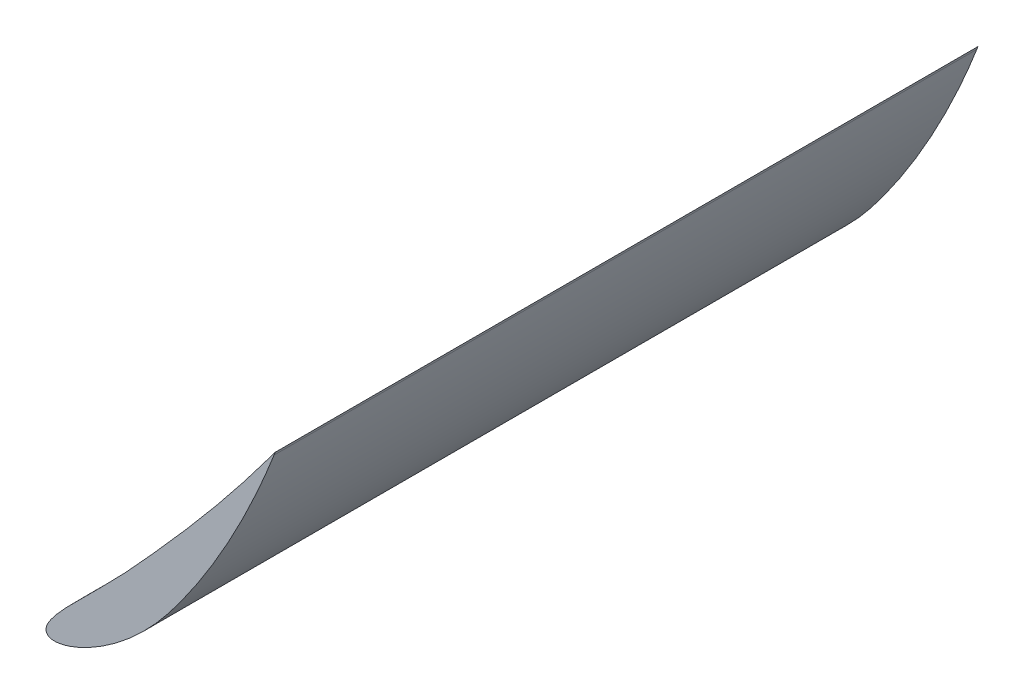
SolidWorks part; units mm, degrees
ref_plane "Front Plane" through (0, 0, 0) normal (0, 0, 1) x (1, 0, 0)
ref_plane "Top Plane" through (0, 0, 0) normal (0, 1, 0) x (1, 0, 0)
ref_plane "Right Plane" through (0, 0, 0) normal (1, 0, 0) x (0, 0, -1)
sketch "Sketch1" plane through (0, 0, 0) normal (0, 0, 1) x (1, 0, 0)
  line L12 (81.634, 97.2876) -> (0, 0) construction
  line L13 (81.5114, 97.3905) -> (81.7566, 97.1848) construction
  line L15 (0, 0) -> (49.9996, 0) construction
  line L16 (81.5114, 97.3905) -> (82.1927, 98.3086)
  line L17 (81.7566, 97.1848) -> (82.1927, 98.3086)
  spline S1 degree 3 poles (81.7566, 97.1848) (81.7317, 97.1205) (81.6321, 96.864) (81.4077, 96.2892) (81.0334, 95.3367) (80.5075, 94.0156) (79.829, 92.3376) (78.9965, 90.3178) (78.0086, 87.974) (76.8643, 85.3265) (75.5632, 82.3981) (74.105, 79.2134) (72.4912, 75.7986) (70.7234, 72.1816) (68.8046, 68.3914) (66.7394, 64.4574) (64.5329, 60.4101) (62.192, 56.2804) (59.7244, 52.0991) (57.1391, 47.8973) (54.4471, 43.705) (51.6593, 39.5528) (48.7894, 35.4693) (45.8491, 31.4847) (42.8637, 27.6176) (39.7792, 23.949) (36.6227, 20.4984) (33.4183, 17.2831) (30.1932, 14.317) (26.9767, 11.6105) (23.7993, 9.1714) (20.6932, 7.004) (17.6904, 5.1108) (14.8237, 3.491) (12.1246, 2.1423) (9.6232, 1.0613) (7.3474, 0.2422) (5.3215, -0.3201) (3.5651, -0.6329) (2.09, -0.7009) (0.8965, -0.5251) (-0.0134, -0.0818) (-0.579, 0.6607) (-0.6886, 1.6321) (-0.4133, 2.7429) (0.1968, 4.0285) (1.138, 5.5031) (2.4006, 7.1704) (3.9718, 9.0291) (5.834, 11.0763) (7.9665, 13.3081) (10.3447, 15.7209) (12.9427, 18.3096) (15.7314, 21.0695) (18.6806, 23.9946) (21.7585, 27.0784) (24.933, 30.313) (28.1717, 33.6891) (31.4437, 37.1956) (34.7151, 40.8229) (38.0269, 44.4942) (41.3443, 48.201) (44.6452, 51.9215) (47.9049, 55.6368) (51.1016, 59.325) (54.2144, 62.9647) (57.224, 66.5334) (60.1133, 70.0079) (62.8659, 73.3655) (65.468, 76.5829) (67.9066, 79.6376) (70.1703, 82.5079) (72.2485, 85.1731) (74.1325, 87.6134) (75.814, 89.8111) (77.286, 91.7497) (78.542, 93.415) (79.577, 94.7947) (80.3867, 95.8784) (80.9673, 96.6583) (81.3169, 97.1284) (81.4725, 97.338) (81.5114, 97.3905) knots 0 0 0 0 0.000791 0.00316 0.007087 0.012544 0.019489 0.027873 0.037633 0.048699 0.060994 0.074433 0.088923 0.104368 0.120665 0.13771 0.155392 0.173601 0.192223 0.211146 0.230254 0.249435 0.268577 0.287568 0.306301 0.324671 0.342595 0.359992 0.376786 0.392898 0.408252 0.422771 0.43638 0.449003 0.46057 0.471014 0.48028 0.488325 0.495133 0.500728 0.505217 0.508863 0.51207 0.515471 0.519696 0.525078 0.53175 0.539754 0.54908 0.559692 0.571531 0.584528 0.598598 0.61365 0.629586 0.6463 0.663686 0.681632 0.700027 0.718761 0.737727 0.756809 0.775888 0.794846 0.813569 0.83194 0.849847 0.86718 0.883834 0.899707 0.914701 0.928723 0.941687 0.953513 0.964128 0.973465 0.981467 0.988083 0.993272 0.997002 0.999249 1 1 1 1
  point P10 (81.634, 97.2876)
  dimension "D1" = 50
  dimension "D2" = 127
extrude "Boss-Extrude1" add sketch "Sketch1" along normal blind 254
sketch "Sketch2" plane through (0, 0, 254) normal (0, 0, 1) x (1, 0, 0)
  line L0 (81.5114, 97.3905) -> (81.7566, 97.1848) construction
  line L1 (81.634, 97.2876) -> (0, 0) construction
  line L2 (81.7566, 97.1848) -> (82.1927, 98.3086)
  line L3 (82.1927, 98.3086) -> (81.5114, 97.3905)
  line L4 (81.7566, 97.1848) -> (82.1927, 98.3086) construction
  line L5 (82.1927, 98.3086) -> (81.5114, 97.3905) construction
  line L6 (0, 0) -> (-10.9759, 9.2098) construction
  spline S1 degree 3 poles (3362.1058, -2188.2174) (124.3808, 166.0181) (105.4022, 129.5143) (80.9673, 96.6583) (80.3867, 95.8784) (79.577, 94.7947) (78.542, 93.415) (77.286, 91.7497) (75.814, 89.8111) (74.1325, 87.6134) (72.2485, 85.1731) (70.1703, 82.5079) (67.9066, 79.6376) (65.468, 76.5829) (62.8659, 73.3655) (60.1133, 70.0079) (57.224, 66.5334) (54.2144, 62.9647) (51.1016, 59.325) (47.9049, 55.6368) (44.6452, 51.9215) (41.3443, 48.201) (38.0269, 44.4942) (34.7151, 40.8229) (31.4437, 37.1956) (28.1717, 33.6891) (24.933, 30.313) (21.7585, 27.0784) (18.6806, 23.9946) (15.7314, 21.0695) (12.9427, 18.3096) (10.3447, 15.7209) (7.9665, 13.3081) (5.834, 11.0763) (3.9718, 9.0291) (2.4006, 7.1704) (1.138, 5.5031) (0.1968, 4.0285) (-0.4133, 2.7429) (-0.6886, 1.6321) (-0.579, 0.6607) (-0.0134, -0.0818) (0.8965, -0.5251) (2.09, -0.7009) (3.5651, -0.6329) (5.3215, -0.3201) (7.3474, 0.2422) (9.6232, 1.0613) (12.1246, 2.1423) (14.8237, 3.491) (17.6904, 5.1108) (20.6932, 7.004) (23.7993, 9.1714) (26.9767, 11.6105) (30.1932, 14.317) (33.4183, 17.2831) (36.6227, 20.4984) (39.7792, 23.949) (42.8637, 27.6176) (45.8491, 31.4847) (48.7894, 35.4693) (51.6593, 39.5528) (54.4471, 43.705) (57.1391, 47.8973) (59.7244, 52.0991) (62.192, 56.2804) (64.5329, 60.4101) (66.7394, 64.4574) (68.8046, 68.3914) (70.7234, 72.1816) (72.4912, 75.7986) (74.105, 79.2134) (75.5632, 82.3981) (76.8643, 85.3265) (78.0086, 87.974) (78.9965, 90.3178) (79.829, 92.3376) (80.5075, 94.0156) (81.0334, 95.3367) (81.4077, 96.2892) (93.9088, 128.314) (98.5574, 163.0245) (3844.0205, -1256.6357) knots -0.463503 -0.463503 -0.463503 -0.463503 0.000751 0.002998 0.006728 0.011917 0.018533 0.026535 0.035872 0.046487 0.058313 0.071277 0.085299 0.100293 0.116166 0.13282 0.150153 0.16806 0.186431 0.205154 0.224112 0.243191 0.262273 0.281239 0.299973 0.318368 0.336314 0.3537 0.370414 0.38635 0.401402 0.415472 0.428469 0.440308 0.45092 0.460246 0.46825 0.474922 0.480304 0.484529 0.48793 0.491137 0.494783 0.499272 0.504867 0.511675 0.51972 0.528986 0.53943 0.550997 0.56362 0.577229 0.591748 0.607102 0.623214 0.640008 0.657405 0.675329 0.693699 0.712432 0.731423 0.750565 0.769746 0.788854 0.807777 0.826399 0.844608 0.86229 0.879335 0.895632 0.911077 0.925567 0.939006 0.951301 0.962367 0.972127 0.980511 0.987456 0.992913 0.99684 0.999209 1.387719 1.387719 1.387719 1.387719 only from (81.5114, 97.3905) to (81.7566, 97.1848)
  spline S2 degree 3 poles (81.5114, 97.3905) (81.4725, 97.338) (81.3169, 97.1284) (80.9673, 96.6583) (80.3867, 95.8784) (79.577, 94.7947) (78.542, 93.415) (77.286, 91.7497) (75.814, 89.8111) (74.1325, 87.6134) (72.2485, 85.1731) (70.1703, 82.5079) (67.9066, 79.6376) (65.468, 76.5829) (62.8659, 73.3655) (60.1133, 70.0079) (57.224, 66.5334) (54.2144, 62.9647) (51.1016, 59.325) (47.9049, 55.6368) (44.6452, 51.9215) (41.3443, 48.201) (38.0269, 44.4942) (34.7151, 40.8229) (31.4437, 37.1956) (28.1717, 33.6891) (24.933, 30.313) (21.7585, 27.0784) (18.6806, 23.9946) (15.7314, 21.0695) (12.9427, 18.3096) (10.3447, 15.7209) (7.9665, 13.3081) (5.834, 11.0763) (3.9718, 9.0291) (2.4006, 7.1704) (1.138, 5.5031) (0.1968, 4.0285) (-0.4133, 2.7429) (-0.6886, 1.6321) (-0.579, 0.6607) (-0.0134, -0.0818) (0.8965, -0.5251) (2.09, -0.7009) (3.5651, -0.6329) (5.3215, -0.3201) (7.3474, 0.2422) (9.6232, 1.0613) (12.1246, 2.1423) (14.8237, 3.491) (17.6904, 5.1108) (20.6932, 7.004) (23.7993, 9.1714) (26.9767, 11.6105) (30.1932, 14.317) (33.4183, 17.2831) (36.6227, 20.4984) (39.7792, 23.949) (42.8637, 27.6176) (45.8491, 31.4847) (48.7894, 35.4693) (51.6593, 39.5528) (54.4471, 43.705) (57.1391, 47.8973) (59.7244, 52.0991) (62.192, 56.2804) (64.5329, 60.4101) (66.7394, 64.4574) (68.8046, 68.3914) (70.7234, 72.1816) (72.4912, 75.7986) (74.105, 79.2134) (75.5632, 82.3981) (76.8643, 85.3265) (78.0086, 87.974) (78.9965, 90.3178) (79.829, 92.3376) (80.5075, 94.0156) (81.0334, 95.3367) (81.4077, 96.2892) (81.6321, 96.864) (81.7317, 97.1205) (81.7566, 97.1848) knots 0 0 0 0 0.000751 0.002998 0.006728 0.011917 0.018533 0.026535 0.035872 0.046487 0.058313 0.071277 0.085299 0.100293 0.116166 0.13282 0.150153 0.16806 0.186431 0.205154 0.224112 0.243191 0.262273 0.281239 0.299973 0.318368 0.336314 0.3537 0.370414 0.38635 0.401402 0.415472 0.428469 0.440308 0.45092 0.460246 0.46825 0.474922 0.480304 0.484529 0.48793 0.491137 0.494783 0.499272 0.504867 0.511675 0.51972 0.528986 0.53943 0.550997 0.56362 0.577229 0.591748 0.607102 0.623214 0.640008 0.657405 0.675329 0.693699 0.712432 0.731423 0.750565 0.769746 0.788854 0.807777 0.826399 0.844608 0.86229 0.879335 0.895632 0.911077 0.925567 0.939006 0.951301 0.962367 0.972127 0.980511 0.987456 0.992913 0.99684 0.999209 1 1 1 1 construction
  dimension "D1" = 0
